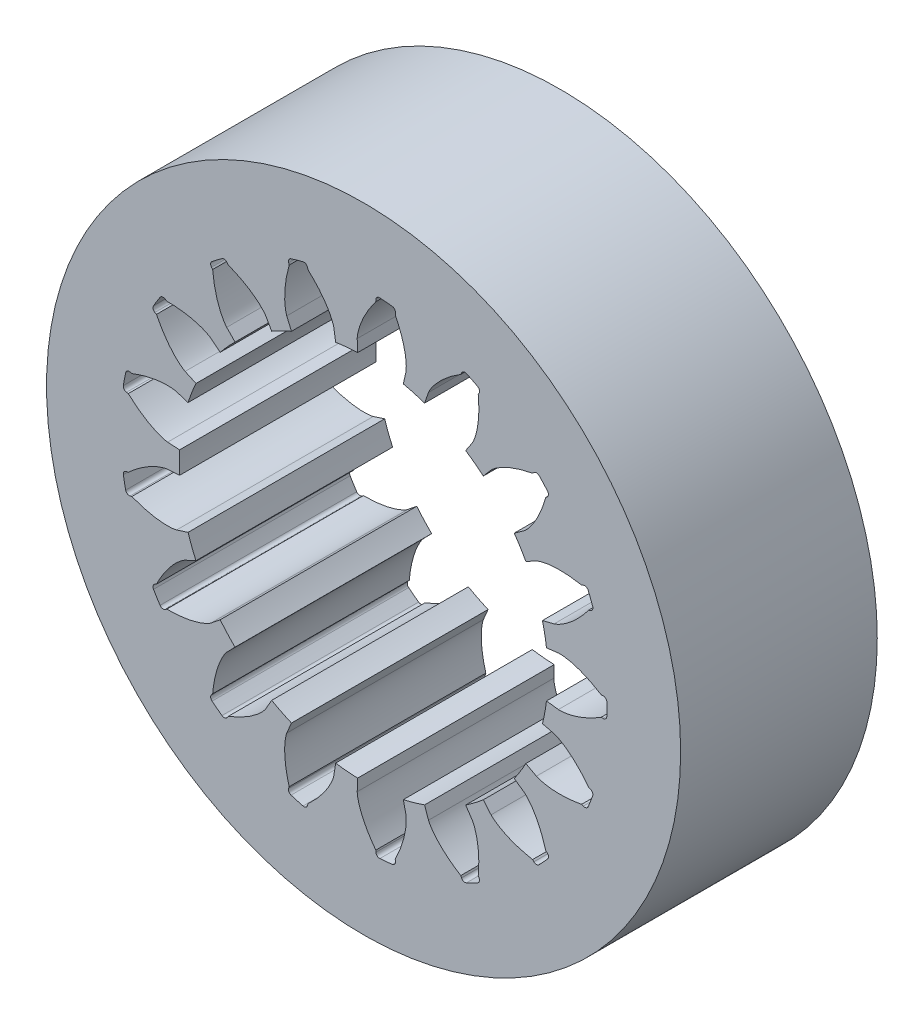
SolidWorks part; units mm, degrees
ref_plane "Front Plane" through (0, 0, 0) normal (0, 0, 1) x (1, 0, 0)
ref_plane "Top Plane" through (0, 0, 0) normal (0, 1, 0) x (1, 0, 0)
ref_plane "Right Plane" through (0, 0, 0) normal (1, 0, 0) x (0, 0, -1)
ref_axis "Gear Axis" through (0, 0, -0.5001) along (0, 0, 1)
sketch "Blank Sketch" plane through (0, 0, 0) normal (0, 0, 1) x (1, 0, 0)
  circle A0 centre (0, 0) radius 16.125
  circle A1 centre (0, 0) radius 9.375
  dimension "Rim" = 32.25
  dimension "Tip" = 18.75
extrude "Blank" add sketch "Blank Sketch" along normal blind 10
sketch "Tooth Space Sketch" plane through (0, 0, 0) normal (0, 0, 1) x (1, 0, 0)
  line L0 (9.9064, 1.2443) -> (8.0617, 1.0126)
  line L1 (9.9064, -1.2443) -> (8.0617, -1.0126)
  line L2 (8.0617, 1.0126) -> (8.0617, -1.0126)
  line L3 (12.0836, 0.4958) -> (12.1758, 0.4996)
  line L4 (12.0836, -0.4958) -> (12.1758, -0.4996)
  circle A0 centre (0, 0) radius 8.125 construction
  arc A1 (12.3709, 0.3171) -> (12.1758, 0.4996) centre (12.1835, 0.3122) ccw
  arc A2 (12.1758, -0.4996) -> (12.3709, -0.3171) centre (12.1835, -0.3122) ccw
  arc A3 (12.3709, -0.3171) -> (12.3709, 0.3171) centre (0, 0) ccw
  spline S0 degree 4 poles (9.9064, 1.2443) (9.9098, 1.2447) (9.9195, 1.2456) (9.9377, 1.2467) (9.9676, 1.2477) (10.0058, 1.2476) (10.0552, 1.2461) (10.1134, 1.2425) (10.1774, 1.2365) (10.247, 1.2278) (10.3164, 1.2173) (10.3856, 1.2051) (10.4544, 1.1914) (10.5377, 1.1729) (10.6373, 1.1482) (10.7533, 1.1155) (10.8845, 1.0741) (11.0174, 1.0272) (11.1477, 0.9773) (11.2786, 0.9224) (11.4047, 0.8662) (11.5347, 0.8034) (11.6543, 0.7432) (11.7872, 0.6709) (11.894, 0.6111) (12.0337, 0.5271) (12.1158, 0.476) (12.2114, 0.4144) (12.2536, 0.3861) (12.2796, 0.3687) knots 0 0 0 0 0 0.005377 0.015084 0.028532 0.04661 0.064855 0.092111 0.119476 0.146842 0.174209 0.201575 0.228941 0.256307 0.307035 0.361767 0.4165 0.471232 0.525964 0.580697 0.635429 0.690161 0.744894 0.799626 0.854358 0.909091 0.954545 1 1 1 1 1 construction
  spline S1 degree 4 poles (9.9064, 1.2443) (9.9098, 1.2447) (9.9195, 1.2456) (9.9377, 1.2467) (9.9676, 1.2477) (10.0058, 1.2476) (10.0552, 1.2461) (10.1134, 1.2425) (10.1774, 1.2365) (10.247, 1.2278) (10.3164, 1.2173) (10.3856, 1.2051) (10.4544, 1.1914) (10.5377, 1.1729) (10.6373, 1.1482) (10.7533, 1.1155) (10.8845, 1.0741) (11.0174, 1.0272) (11.1477, 0.9773) (11.2786, 0.9224) (11.4047, 0.8662) (11.5347, 0.8034) (11.6543, 0.7432) (11.7872, 0.6709) (11.894, 0.6111) (12.0034, 0.5453) (12.0565, 0.5127) (12.0836, 0.4958) knots 0 0 0 0 0 0.005377 0.015084 0.028532 0.04661 0.064855 0.092111 0.119476 0.146842 0.174209 0.201575 0.228941 0.256307 0.307035 0.361767 0.4165 0.471232 0.525964 0.580697 0.635429 0.690161 0.744894 0.799626 0.854358 0.909091 0.909091 0.909091 0.909091 0.909091
  spline S2 degree 4 poles (9.9064, -1.2443) (9.9098, -1.2447) (9.9195, -1.2456) (9.9377, -1.2467) (9.9676, -1.2477) (10.0058, -1.2476) (10.0552, -1.2461) (10.1134, -1.2425) (10.1774, -1.2365) (10.247, -1.2278) (10.3164, -1.2173) (10.3856, -1.2051) (10.4544, -1.1914) (10.5377, -1.1729) (10.6373, -1.1482) (10.7533, -1.1155) (10.8845, -1.0741) (11.0174, -1.0272) (11.1477, -0.9773) (11.2786, -0.9224) (11.4047, -0.8662) (11.5347, -0.8034) (11.6543, -0.7432) (11.7872, -0.6709) (11.894, -0.6111) (12.0337, -0.5271) (12.1158, -0.476) (12.2114, -0.4144) (12.2536, -0.3861) (12.2796, -0.3687) knots 0 0 0 0 0 0.005377 0.015084 0.028532 0.04661 0.064855 0.092111 0.119476 0.146842 0.174209 0.201575 0.228941 0.256307 0.307035 0.361767 0.4165 0.471232 0.525964 0.580697 0.635429 0.690161 0.744894 0.799626 0.854358 0.909091 0.954545 1 1 1 1 1 construction
  spline S3 degree 4 poles (9.9064, -1.2443) (9.9098, -1.2447) (9.9195, -1.2456) (9.9377, -1.2467) (9.9676, -1.2477) (10.0058, -1.2476) (10.0552, -1.2461) (10.1134, -1.2425) (10.1774, -1.2365) (10.247, -1.2278) (10.3164, -1.2173) (10.3856, -1.2051) (10.4544, -1.1914) (10.5377, -1.1729) (10.6373, -1.1482) (10.7533, -1.1155) (10.8845, -1.0741) (11.0174, -1.0272) (11.1477, -0.9773) (11.2786, -0.9224) (11.4047, -0.8662) (11.5347, -0.8034) (11.6543, -0.7432) (11.7872, -0.6709) (11.894, -0.6111) (12.0034, -0.5453) (12.0565, -0.5127) (12.0836, -0.4958) knots 0 0 0 0 0 0.005377 0.015084 0.028532 0.04661 0.064855 0.092111 0.119476 0.146842 0.174209 0.201575 0.228941 0.256307 0.307035 0.361767 0.4165 0.471232 0.525964 0.580697 0.635429 0.690161 0.744894 0.799626 0.854358 0.909091 0.909091 0.909091 0.909091 0.909091
  dimension "Root" = 12.375
  dimension "Fillet" = 0.1875
  dimension "Cap" = 16.25
extrude "Tooth Space" cut sketch "Tooth Space Sketch" against normal through all both and the other way through all both
pattern_circular "Teeth" count 17 over 360 about axis through (0, 0, -0.5001) along (0, 0, 1) of "Tooth Space"
equation "\"No. of Teeth\"= 17"
equation "\"Module\"= 1.25"
equation "\"Pressure Angle\"= 20"
equation "\"Inner Diameter\"= ( \"No. of Teeth\" - 2 ) * \"Module\""
equation "\"Pitch Diameter\"= \"No. of Teeth\" * \"Module\""
equation "\"Backlash\"= 0.3 * \"Module\""
equation "\"Arc Length\"= ( ( \"Module\" * pi ) / 2 + \"Backlash\" )"
equation "\"Fillet Radius\"= 0.15 * \"Module\""
equation "\"Tooth Depth\"= IIF ( \"Module\" <= 1.25 , \"Module\" * 2.4 , \"Module\" * 2.25 )"
equation "\"Face Width\"= 10"
equation "\"Root Diameter\"= \"Inner Diameter\" + 2 * \"Tooth Depth\""
equation "\"Rim Diameter\"= \"Root Diameter\" + 6 * \"Module\""
equation "\"Base Diameter\"= \"Pitch Diameter\" * cos ( \"Pressure Angle\" )"
equation "\"Base Radius\"= \"Base Diameter\" / 2"
equation "\"Tooth Thickness\"= \"Module\" * pi - \"Arc Length\""
equation "\"Half Space Angle\"= ( \"Arc Length\" / \"Pitch Diameter\" ) * 180 / pi"
equation "\"Involute Fn\"= tan ( \"Pressure Angle\" ) - \"Pressure Angle\" * pi / 180"
equation "\"Flank Offset\"= 0 - \"Arc Length\" / \"Pitch Diameter\" - \"Involute Fn\""
equation "\"Tip Cap Diameter\"= \"Inner Diameter\" - 2 * \"Module\""
equation "\"Flank Start Diameter\"= IIF ( \"Base Diameter\" >= ( \"Inner Diameter\" - \"Module\" ) , \"Base Diameter\" , \"Inner Diameter\" - \"Module\" )"
equation "\"Flank End Diameter\"= \"Root Diameter\" - 3 * \"Fillet Radius\""
equation "\"Involute t1\"= ( abs ( ( \"Flank Start Diameter\" / \"Base Diameter\" ) ^ 2 - 1 ) ) ^ 0.5"
equation "\"Involute t2\"= ( abs ( ( \"Flank End Diameter\" / \"Base Diameter\" ) ^ 2 - 1 ) ) ^ 0.5"
equation "\"Flank Arc Radius\"= ( \"Pitch Diameter\" / 2 ) * sin ( \"Pressure Angle\" )"
equation "\"Flank Centre Angle\"= \"Half Space Angle\" - \"Pressure Angle\""
equation "\"Rim@Blank Sketch\"= \"Rim Diameter\""
equation "\"Tip@Blank Sketch\"= \"Inner Diameter\""
equation "\"Width@Blank\"= \"Face Width\""
equation "\"Root@Tooth Space Sketch\"= \"Root Diameter\" / 2"
equation "\"Fillet@Tooth Space Sketch\"= \"Fillet Radius\""
equation "\"Cap@Tooth Space Sketch\"= \"Tip Cap Diameter\""
equation "\"Count@Teeth\"= \"No. of Teeth\""
